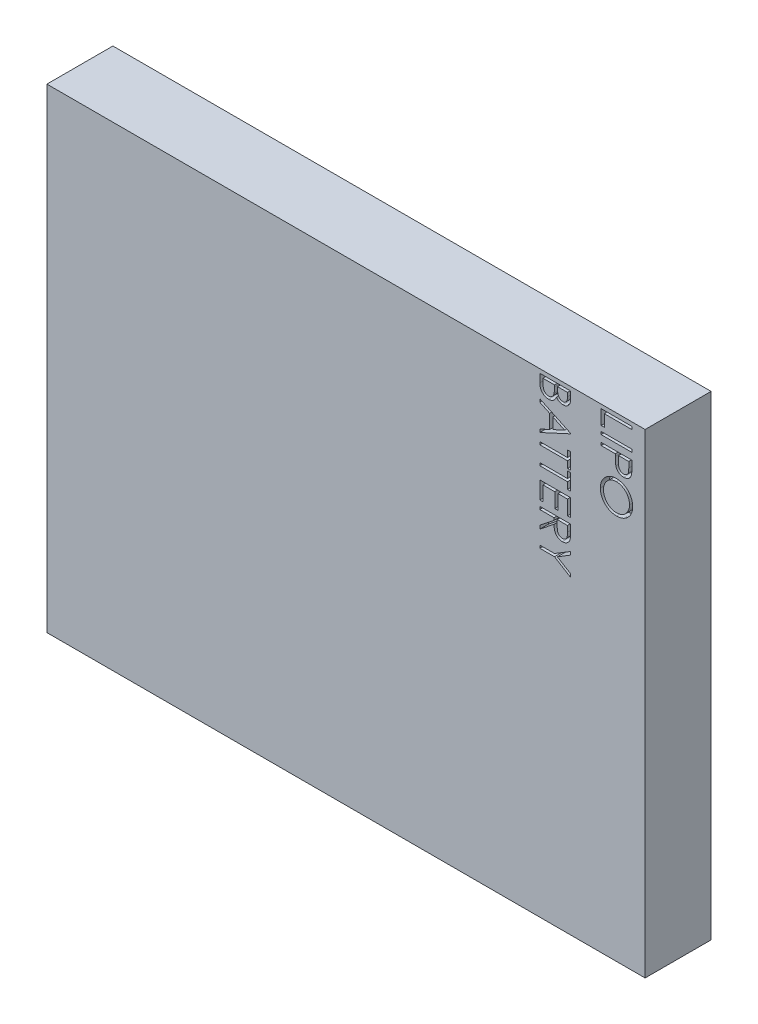
SolidWorks part; units mm, degrees
ref_plane "Front Plane" through (0, 0, 0) normal (0, 0, 1) x (1, 0, 0)
ref_plane "Top Plane" through (0, 0, 0) normal (0, 1, 0) x (1, 0, 0)
ref_plane "Right Plane" through (0, 0, 0) normal (1, 0, 0) x (0, 0, -1)
sketch "Sketch1" plane through (0, 0, 0) normal (0, 0, 1) x (1, 0, 0)
  line L1 (-34, 27) -> (34, 27)
  line L2 (-34, 27) -> (-34, -27)
  line L3 (-34, -27) -> (34, -27)
  line L4 (34, 27) -> (34, -27)
  line L5 (-34, 27) -> (34, -27) construction
  line L6 (-34, -27) -> (34, 27) construction
  point P0 (0, 0)
  dimension "D1" = 68
  dimension "D2" = 54
extrude "Boss-Extrude1" add sketch "Sketch1" along normal blind 7.5
sketch "Sketch2" plane through (0, 0, 7.5) normal (0, 0, 1) x (1, 0, 0)
  line L0 (29, 27) -> (29, -27) construction
  line L1 (34, 27) -> (-34, 27) construction
  line L2 (-34, -27) -> (34, -27) construction
  line L3 (34, -27) -> (34, 27) construction
  text T0 "LIPO\r\nBATTERY"
  dimension "D1" = 5
extrude "Cut-Extrude1" cut sketch "Sketch2" against normal blind 1
